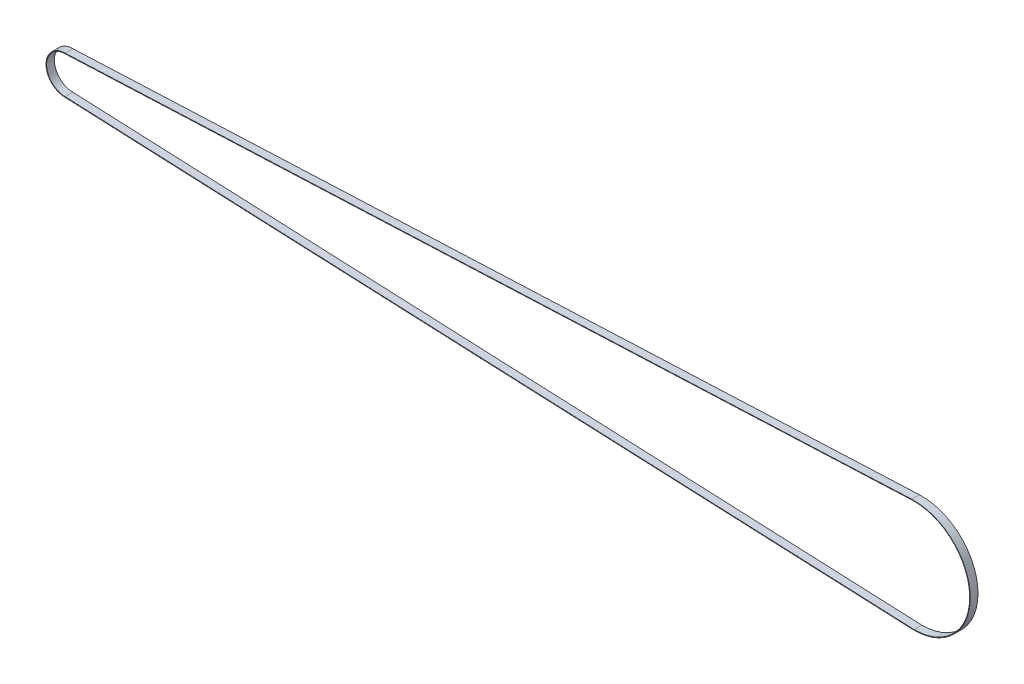
SolidWorks part; units mm, degrees
ref_plane "Front Plane" through (0, 0, 0) normal (0, 0, 1) x (1, 0, 0)
ref_plane "Top Plane" through (0, 0, 0) normal (0, 1, 0) x (1, 0, 0)
ref_plane "Right Plane" through (0, 0, 0) normal (1, 0, 0) x (0, 0, -1)
sketch "Sketch1" plane through (0, 0, 0) normal (0, 0, 1) x (1, 0, 0)
  line L0 (-3.9942, 91.3527) -> (-1396.238, 30.48)
  line L3 (-1396.238, -30.48) -> (0, -91.44)
  line L4 (-1396.238, 31.497) -> (-4.029, 92.2811)
  line L5 (-1396.238, -31.497) -> (-4.029, -92.2811)
  arc A2 (-1396.238, 30.48) -> (-1396.238, -30.48) centre (-1396.238, 0) ccw
  arc A4 (-3.9942, 91.3527) -> (0, -91.44) centre (0, 0) cw
  arc A5 (-4.029, 92.2811) -> (-4.029, -92.2811) centre (0, 0) cw
  arc A6 (-1396.238, -31.497) -> (-1396.238, 31.497) centre (-1396.238, 0) cw
  dimension "D2" = 91.44
  dimension "D3" = 1396.238
  dimension "D1" = 30.48
  dimension "D4" = 1.016
extrude "Boss-Extrude1" add sketch "Sketch1" along normal blind 12.7
